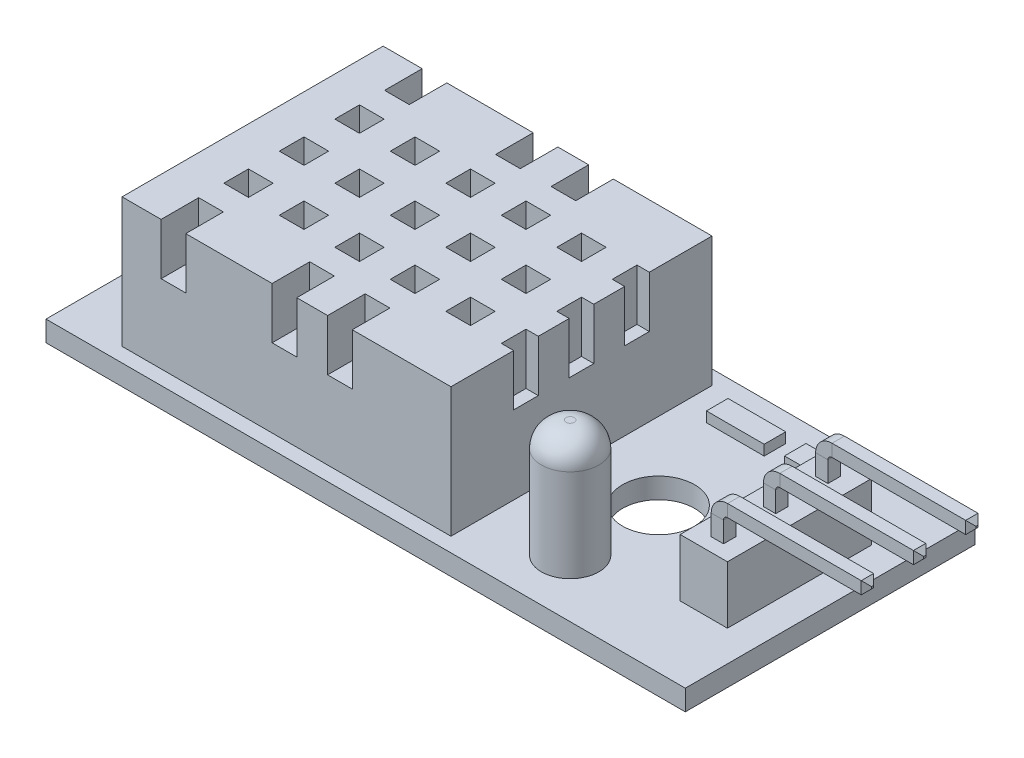
SolidWorks part; units mm, degrees
material "Ст3 ГОСТ 535-2005"
ref_plane "Спереди" through (0, 0, 0) normal (0, 0, 1) x (1, 0, 0)
ref_plane "Сверху" through (0, 0, 0) normal (0, 1, 0) x (1, 0, 0)
ref_plane "Справа" through (0, 0, 0) normal (1, 0, 0) x (0, 0, -1)
sketch "Эскиз1" plane through (0, 0, 0) normal (0, 1, 0) x (1, 0, 0)
  line L1 (-15.55, 7.05) -> (15.55, 7.05)
  line L2 (-15.55, 7.05) -> (-15.55, -7.05)
  line L3 (-15.55, -7.05) -> (15.55, -7.05)
  line L4 (15.55, 7.05) -> (15.55, -7.05)
  line L5 (-15.55, 7.05) -> (15.55, -7.05) construction
  line L6 (-15.55, -7.05) -> (15.55, 7.05) construction
  point P0 (0, 0)
  dimension "D1" = 31.1
  dimension "D2" = 14.1
extrude "Бобышка-Вытянуть1" add sketch "Эскиз1" along normal blind 1
sketch "Эскиз2" plane through (0, 1, 0) normal (0, 1, 0) x (1, 0, 0)
  line L0 (-15.55, 0) -> (15.55, 0) construction
  line L1 (-15.55, 7.05) -> (-15.55, -7.05) construction
  line L2 (15.55, -7.05) -> (15.55, 7.05) construction
  line L4 (-12.55, 6.35) -> (3.45, 6.35)
  line L5 (-12.55, 6.35) -> (-12.55, -6.35)
  line L6 (-12.55, -6.35) -> (3.45, -6.35)
  line L7 (3.45, 6.35) -> (3.45, -6.35)
  line L8 (-12.55, 6.35) -> (3.45, -6.35) construction
  line L9 (-12.55, -6.35) -> (3.45, 6.35) construction
  point P6 (-4.55, 0)
  dimension "D1" = 3
  dimension "D2" = 16
  dimension "D3" = 12.7
extrude "Бобышка-Вытянуть2" add sketch "Эскиз2" along normal blind 6.3
sketch "Эскиз3" plane through (0, 1, 0) normal (0, 1, 0) x (1, 0, 0)
  line L0 (-15.55, 0) -> (15.55, 0) construction
  circle A0 centre (7.2, 0) radius 1.75
  dimension "D1" = 3.5
  dimension "D2" = 6.6
extrude "Вырез-Вытянуть1" cut sketch "Эскиз3" against normal through all
sketch "Эскиз4" plane through (0, 1, 0) normal (0, 1, 0) x (1, 0, 0)
  line L0 (15.55, -7.05) -> (15.55, 7.05) construction
  line L1 (-15.55, -7.05) -> (15.55, -7.05) construction
  circle A0 centre (7.15, -4.25) radius 1.4
  dimension "D1" = 2.8
  dimension "D2" = 9.8
  dimension "D3" = 4.2
extrude "Бобышка-Вытянуть3" add sketch "Эскиз4" along normal blind 5.7
fillet "Скругление1" radius 1.2 1 edges at (7.15, 6.7, 5.65)
sketch "Эскиз5" plane through (0, 1, 0) normal (0, 1, 0) x (1, 0, 0)
  line L0 (-15.55, 0) -> (15.55, 0) construction
  line L1 (11.75, 3.5) -> (14.05, 3.5)
  line L2 (11.75, 3.5) -> (11.75, -3.5)
  line L3 (11.75, -3.5) -> (14.05, -3.5)
  line L4 (14.05, 3.5) -> (14.05, -3.5)
  line L5 (11.75, 3.5) -> (14.05, -3.5) construction
  line L6 (11.75, -3.5) -> (14.05, 3.5) construction
  line L7 (15.55, -7.05) -> (15.55, 7.05) construction
  point P0 (12.9, 0)
  dimension "D1" = 7
  dimension "D2" = 2.3
  dimension "D3" = 3.8
extrude "Бобышка-Вытянуть4" add sketch "Эскиз5" along normal blind 2.8
sketch "Эскиз6" plane through (0, 3.8, 0) normal (0, 1, 0) x (1, 0, 0)
  line L0 (12.9, 3.5) -> (12.9, -3.5) construction
  line L1 (14.05, 3.5) -> (11.75, 3.5) construction
  line L2 (11.75, -3.5) -> (14.05, -3.5) construction
  line L4 (12.6, 0.3) -> (13.2, 0.3)
  line L5 (12.6, 0.3) -> (12.6, -0.3)
  line L6 (12.6, -0.3) -> (13.2, -0.3)
  line L7 (13.2, 0.3) -> (13.2, -0.3)
  line L8 (12.6, 0.3) -> (13.2, -0.3) construction
  line L9 (12.6, -0.3) -> (13.2, 0.3) construction
  point P6 (12.9, 0)
  point P7 (12.9, 0)
  dimension "D1" = 0.6
sketch3d "Трехмерный эскиз1"
  line L0 (12.9, 3.8, 0) -> (12.9, 4.8, 0)
  line L1 (13.4, 5.3, 0) -> (20.15, 5.3, 0)
  arc A0 (12.9, 4.8, 0) -> (13.4, 5.3, 0) centre (13.4, 4.8, 0) ccw
  point P9 (12.9, 5.3, 0)
  point P10 (13.4, 4.8, -0.5)
  dimension "D3" = 0.5
  dimension "D1" = 5.3
  dimension "D2" = 8.4
sweep "По траектории1" add profiles "Эскиз6" path "Трехмерный эскиз1"
pattern_linear "Линейный массив1" count 2 spacing 2.54 along (0, 0, 1) of "По траектории1"
pattern_linear "Линейный массив2" count 2 spacing 2.54 along (0, 0, -1) of "По траектории1"
chamfer "Фаска1" distance 0.25 angle 45 12 edges at (20.15, 5.3, 0.3) (20.15, 5.6, 0) (20.15, 5.3, -0.3) (20.15, 5, 0) (20.15, 5.3, 2.84) (20.15, 5.6, 2.54) (20.15, 5.3, 2.24) (20.15, 5, 2.54) (20.15, 5.3, -2.24) (20.15, 5.6, -2.54) (20.15, 5.3, -2.84) (20.15, 5, -2.54)
sketch "Эскиз7" plane through (0, 1, 0) normal (0, 1, 0) x (1, 0, 0)
  line L1 (4.8833, 5.6952) -> (7.6914, 5.6952)
  line L2 (4.8833, 5.6952) -> (4.8833, 4.646)
  line L3 (4.8833, 4.646) -> (7.6914, 4.646)
  line L4 (7.6914, 5.6952) -> (7.6914, 4.646)
  line L5 (8.6789, 5.6952) -> (11.2094, 5.6952)
  line L6 (8.6789, 5.6952) -> (8.6789, 4.646)
  line L7 (8.6789, 4.646) -> (11.2094, 4.646)
  line L8 (11.2094, 5.6952) -> (11.2094, 4.646)
extrude "Бобышка-Вытянуть5" add sketch "Эскиз7" along normal blind 0.5
sketch "Эскиз8" plane through (-12.55, 0, 0) normal (-1, 0, 0) x (0, 0, 1)
  line L0 (-6.35, 3.6) -> (6.35, 3.6) construction
  line L1 (-6.35, 7.3) -> (-6.35, 1) construction
  line L2 (6.35, 7.3) -> (6.35, 1) construction
  line L3 (0, 0) -> (0, 3.6) construction
  circle A0 centre (-5, 3.6) radius 0.15
  point P6 (-5, 3.6)
  point P7 (-2.5, 3.6)
  point P8 (2.5, 3.6)
  point P9 (5, 3.6)
  dimension "D4" = 0.3
  dimension "D1" = 2.5
  dimension "D2" = 2.5
  dimension "D3" = 3.6
sketch3d "Трехмерный эскиз2"
  line L0 (-12.55, 3.6, -5) -> (-12.9997, 3.6, -5)
  line L1 (-13.4997, 3.1, -5) -> (-13.4997, 1, -5)
  arc A0 (-12.9997, 3.6, -5) -> (-13.4997, 3.1, -5) centre (-12.9997, 3.1, -5) ccw
  point P6 (-13.4997, 3.6, -5)
  point P7 (-12.9997, 3.1, -4.5)
  dimension "D1" = 0.5
sweep "По траектории2" add profiles "Эскиз8" path "Трехмерный эскиз2"
pattern_linear "Линейный массив3" count 4 spacing 3.3 along (0, 0, 1) of "По траектории2"
sketch "Эскиз9" plane through (0, 7.3, 0) normal (0, 1, 0) x (1, 0, 0)
  line L0 (3.45, 6.35) -> (3.45, -6.35) construction
  line L1 (2.85, 0.6) -> (4.05, 0.6)
  line L2 (2.85, 0.6) -> (2.85, -0.6)
  line L3 (2.85, -0.6) -> (4.05, -0.6)
  line L4 (4.05, 0.6) -> (4.05, -0.6)
  line L5 (2.85, 0.6) -> (4.05, -0.6) construction
  line L6 (2.85, -0.6) -> (4.05, 0.6) construction
  line L7 (0.15, 0.6) -> (1.35, 0.6)
  line L8 (0.15, 0.6) -> (0.15, -0.6)
  line L9 (0.15, -0.6) -> (1.35, -0.6)
  line L10 (1.35, 0.6) -> (1.35, -0.6)
  line L11 (-2.55, 0.6) -> (-1.35, 0.6)
  line L12 (-2.55, 0.6) -> (-2.55, -0.6)
  line L13 (-2.55, -0.6) -> (-1.35, -0.6)
  line L14 (-1.35, 0.6) -> (-1.35, -0.6)
  line L15 (-5.25, 0.6) -> (-4.05, 0.6)
  line L16 (-5.25, 0.6) -> (-5.25, -0.6)
  line L17 (-5.25, -0.6) -> (-4.05, -0.6)
  line L18 (-4.05, 0.6) -> (-4.05, -0.6)
  line L19 (-7.95, 0.6) -> (-6.75, 0.6)
  line L20 (-7.95, 0.6) -> (-7.95, -0.6)
  line L21 (-7.95, -0.6) -> (-6.75, -0.6)
  line L22 (-6.75, 0.6) -> (-6.75, -0.6)
  line L23 (-10.65, 0.6) -> (-9.45, 0.6)
  line L24 (-10.65, 0.6) -> (-10.65, -0.6)
  line L25 (-10.65, -0.6) -> (-9.45, -0.6)
  line L26 (-9.45, 0.6) -> (-9.45, -0.6)
  line L27 (2.85, 3.3) -> (4.05, 3.3)
  line L28 (2.85, 3.3) -> (2.85, 2.1)
  line L29 (2.85, 2.1) -> (4.05, 2.1)
  line L30 (4.05, 3.3) -> (4.05, 2.1)
  line L31 (0.15, 3.3) -> (1.35, 3.3)
  line L32 (0.15, 3.3) -> (0.15, 2.1)
  line L33 (0.15, 2.1) -> (1.35, 2.1)
  line L34 (1.35, 3.3) -> (1.35, 2.1)
  line L35 (-2.55, 3.3) -> (-1.35, 3.3)
  line L36 (-2.55, 3.3) -> (-2.55, 2.1)
  line L37 (-2.55, 2.1) -> (-1.35, 2.1)
  line L38 (-1.35, 3.3) -> (-1.35, 2.1)
  line L39 (-5.25, 3.3) -> (-4.05, 3.3)
  line L40 (-5.25, 3.3) -> (-5.25, 2.1)
  line L41 (-5.25, 2.1) -> (-4.05, 2.1)
  line L42 (-4.05, 3.3) -> (-4.05, 2.1)
  line L43 (-7.95, 3.3) -> (-6.75, 3.3)
  line L44 (-7.95, 3.3) -> (-7.95, 2.1)
  line L45 (-7.95, 2.1) -> (-6.75, 2.1)
  line L46 (-6.75, 3.3) -> (-6.75, 2.1)
  line L47 (-10.65, 3.3) -> (-9.45, 3.3)
  line L48 (-10.65, 3.3) -> (-10.65, 2.1)
  line L49 (-10.65, 2.1) -> (-9.45, 2.1)
  line L50 (-9.45, 3.3) -> (-9.45, 2.1)
  line L51 (2.85, 3.3) -> (4.05, 2.1) construction
  line L52 (2.85, 2.1) -> (4.05, 3.3) construction
  line L53 (2.85, -2.1) -> (4.05, -2.1)
  line L54 (2.85, -2.1) -> (2.85, -3.3)
  line L55 (2.85, -3.3) -> (4.05, -3.3)
  line L56 (4.05, -2.1) -> (4.05, -3.3)
  line L57 (0.15, -2.1) -> (1.35, -2.1)
  line L58 (0.15, -2.1) -> (0.15, -3.3)
  line L59 (0.15, -3.3) -> (1.35, -3.3)
  line L60 (1.35, -2.1) -> (1.35, -3.3)
  line L61 (-2.55, -2.1) -> (-1.35, -2.1)
  line L62 (-2.55, -2.1) -> (-2.55, -3.3)
  line L63 (-2.55, -3.3) -> (-1.35, -3.3)
  line L64 (-1.35, -2.1) -> (-1.35, -3.3)
  line L65 (-5.25, -2.1) -> (-4.05, -2.1)
  line L66 (-5.25, -2.1) -> (-5.25, -3.3)
  line L67 (-5.25, -3.3) -> (-4.05, -3.3)
  line L68 (-4.05, -2.1) -> (-4.05, -3.3)
  line L69 (-7.95, -2.1) -> (-6.75, -2.1)
  line L70 (-7.95, -2.1) -> (-7.95, -3.3)
  line L71 (-7.95, -3.3) -> (-6.75, -3.3)
  line L72 (-6.75, -2.1) -> (-6.75, -3.3)
  line L73 (-10.65, -2.1) -> (-9.45, -2.1)
  line L74 (-10.65, -2.1) -> (-10.65, -3.3)
  line L75 (-10.65, -3.3) -> (-9.45, -3.3)
  line L76 (-9.45, -2.1) -> (-9.45, -3.3)
  line L77 (2.85, -2.1) -> (4.05, -3.3) construction
  line L78 (2.85, -3.3) -> (4.05, -2.1) construction
  line L79 (-12.55, 6.35) -> (3.45, 6.35) construction
  line L80 (-10.65, 6.35) -> (-9.45, 6.35)
  line L81 (-10.65, 6.35) -> (-10.65, 4.5212)
  line L82 (-10.65, 4.5212) -> (-9.45, 4.5212)
  line L83 (-9.45, 6.35) -> (-9.45, 4.5212)
  line L84 (-12.55, 0) -> (3.45, 0) construction
  line L85 (-5.25, 6.35) -> (-4.05, 6.35)
  line L86 (-5.25, 6.35) -> (-5.25, 4.5212)
  line L87 (-5.25, 4.5212) -> (-4.05, 4.5212)
  line L88 (-4.05, 6.35) -> (-4.05, 4.5212)
  line L89 (-2.55, 6.35) -> (-1.35, 6.35)
  line L90 (-2.55, 6.35) -> (-2.55, 4.5212)
  line L91 (-2.55, 4.5212) -> (-1.35, 4.5212)
  line L92 (-1.35, 6.35) -> (-1.35, 4.5212)
  line L93 (-12.55, 6.35) -> (-12.55, -6.35) construction
  line L94 (-1.35, -6.35) -> (-1.35, -4.5212)
  line L95 (-2.55, -4.5212) -> (-1.35, -4.5212)
  line L96 (-2.55, -6.35) -> (-2.55, -4.5212)
  line L97 (-2.55, -6.35) -> (-1.35, -6.35)
  line L98 (-4.05, -6.35) -> (-4.05, -4.5212)
  line L99 (-5.25, -4.5212) -> (-4.05, -4.5212)
  line L100 (-5.25, -6.35) -> (-5.25, -4.5212)
  line L101 (-5.25, -6.35) -> (-4.05, -6.35)
  line L102 (-9.45, -6.35) -> (-9.45, -4.5212)
  line L103 (-10.65, -4.5212) -> (-9.45, -4.5212)
  line L104 (-10.65, -6.35) -> (-10.65, -4.5212)
  line L105 (-10.65, -6.35) -> (-9.45, -6.35)
  point P0 (3.45, 0)
  point P8 (3.45, -2.7)
  point P28 (3.45, 2.7)
  dimension "D1" = 1.2
  dimension "D2" = 6
  dimension "D3" = 2
  dimension "D4" = 2
extrude "Вырез-Вытянуть2" cut sketch "Эскиз9" against normal blind 2.5
